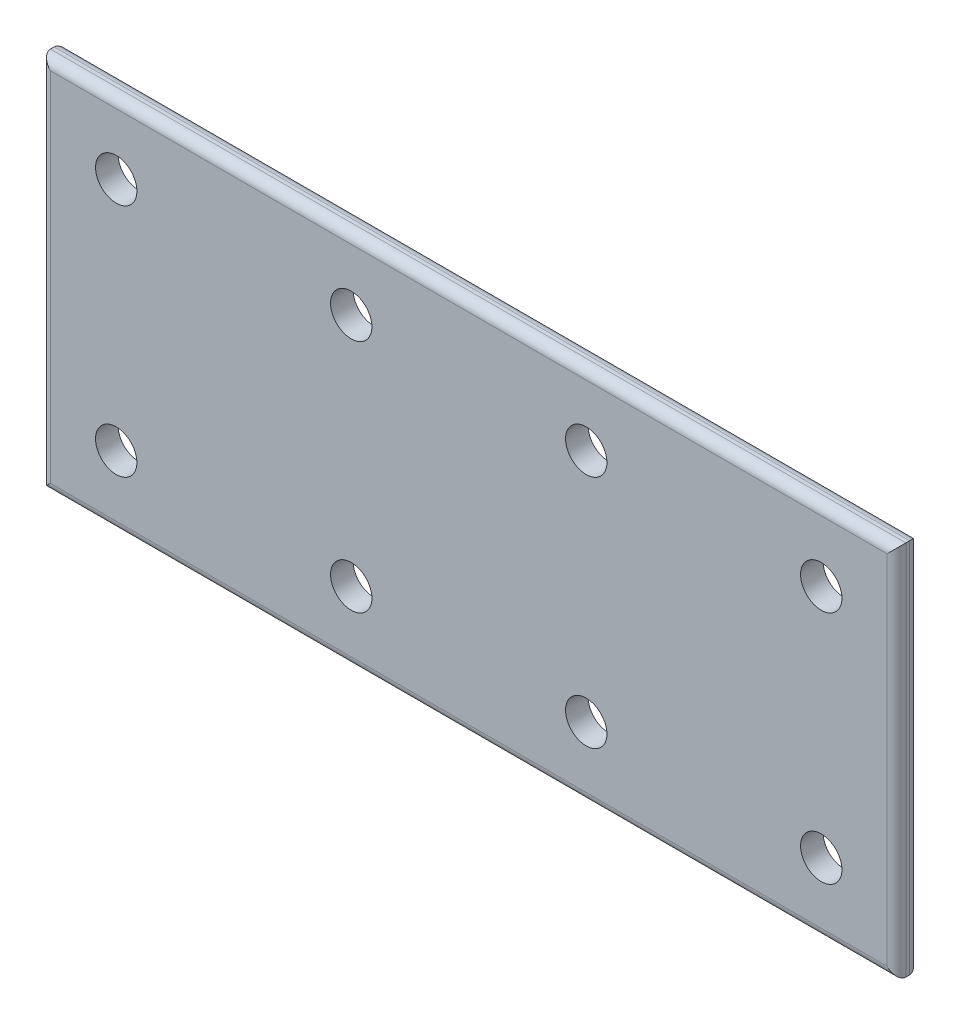
SolidWorks part; units mm, degrees
ref_plane "前视基准面" through (0, 0, 0) normal (0, 0, 1) x (1, 0, 0)
ref_plane "上视基准面" through (0, 0, 0) normal (0, 1, 0) x (1, 0, 0)
ref_plane "右视基准面" through (0, 0, 0) normal (1, 0, 0) x (0, 0, -1)
sketch "草图1" plane through (0, 0, 0) normal (0, 0, 1) x (1, 0, 0)
  line L1 (0, 0) -> (455, 0)
  line L2 (0, 0) -> (0, 200)
  line L3 (0, 200) -> (455, 200)
  line L4 (455, 0) -> (455, 200)
  dimension "D1" = 455
  dimension "D2" = 200
extrude "拉伸1" add sketch "草图1" along normal blind 12
sketch "草图2" plane through (0, 0, 12) normal (0, 0, 1) x (1, 0, 0)
  line L0 (0, 200) -> (0, 0) construction
  line L1 (0, 0) -> (455, 0) construction
  circle A0 centre (40, 37.5) radius 11
  dimension "D1" = 40
  dimension "D3" = 22
  dimension "D2" = 37.5
extrude "拉伸2" cut sketch "草图2" against normal through all
pattern_linear "阵列(线性)1" count 4 spacing 125 along (1, 0, 0) count 2 spacing 125 along (0, 1, 0) of "拉伸2"
fillet "圆角1" radius 5 4 edges at (455, 100, 12) (227.5, 0, 12) (0, 100, 12) (227.5, 200, 12)
fillet "圆角2" radius 5 4 edges at (0, 100, 0) (227.5, 0, 0) (455, 100, 0) (227.5, 200, 0)
